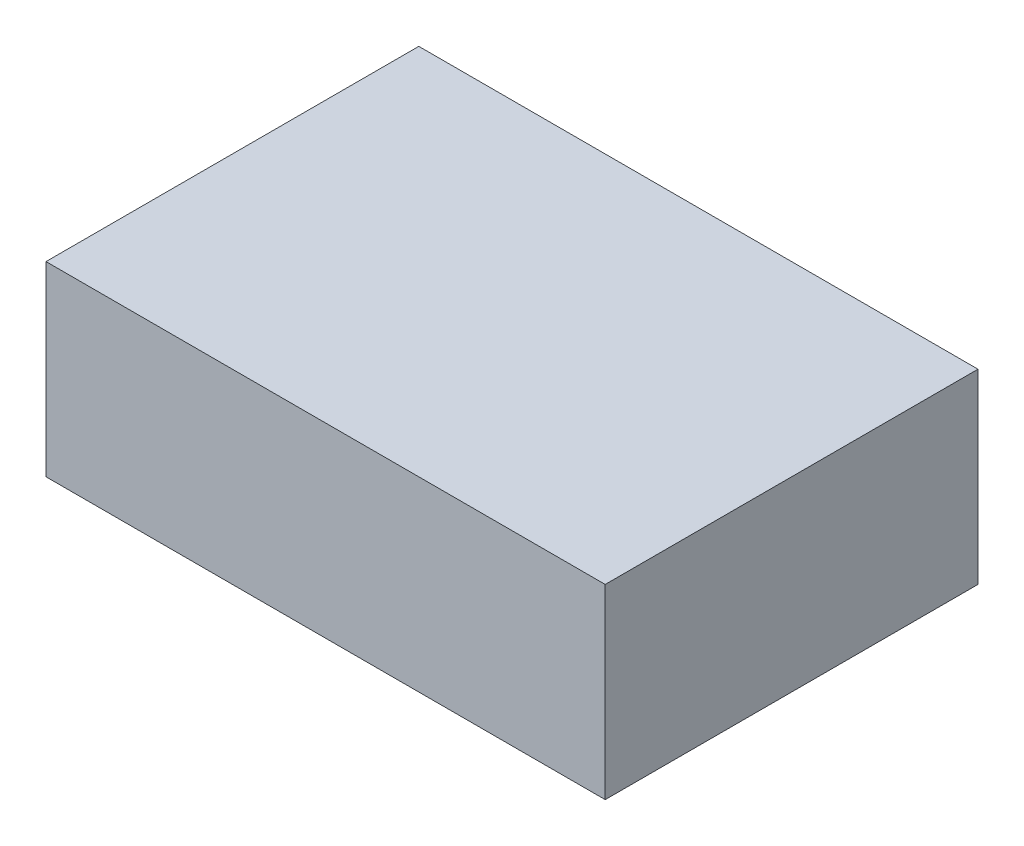
SolidWorks part; units mm, degrees
ref_plane "Front Plane" through (0, 0, 0) normal (0, 0, 1) x (1, 0, 0)
ref_plane "Top Plane" through (0, 0, 0) normal (0, 1, 0) x (1, 0, 0)
ref_plane "Right Plane" through (0, 0, 0) normal (1, 0, 0) x (0, 0, -1)
sketch "Sketch1" plane through (0, 0, 0) normal (0, 0, 1) x (1, 0, 0)
  line L1 (0, 0) -> (150, 0)
  line L2 (0, 0) -> (0, 50)
  line L3 (0, 50) -> (150, 50)
  line L4 (150, 0) -> (150, 50)
  dimension "D1" = 150
  dimension "D2" = 50
extrude "Boss-Extrude1" add sketch "Sketch1" along normal blind 100
sketch "Sketch2" plane through (0, 0, 0) normal (0, -1, 0) x (1, 0, 0)
  line L0 (0, 100) -> (0, 0) construction
  line L1 (0, 85) -> (53.647, 85)
  line L2 (0, 85) -> (0, 15)
  line L3 (0, 15) -> (53.647, 15)
  line L4 (53.647, 85) -> (53.647, 15)
  line L5 (0, 100) -> (150, 100) construction
  line L6 (0, 0) -> (150, 0) construction
  dimension "D1" = 15
  dimension "D2" = 15
extrude "Cut-Extrude1" cut sketch "Sketch2" against normal blind 30
